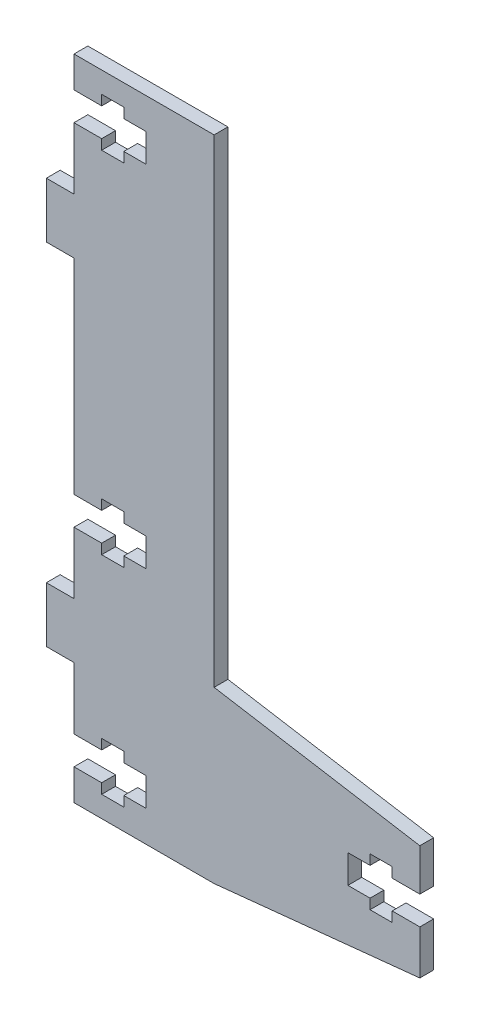
SolidWorks part; units mm, degrees
ref_plane "前视基准面" through (0, 0, 0) normal (0, 0, 1) x (1, 0, 0)
ref_plane "上视基准面" through (0, 0, 0) normal (0, 1, 0) x (1, 0, 0)
ref_plane "右视基准面" through (0, 0, 0) normal (1, 0, 0) x (0, 0, -1)
sketch "草图1" plane through (0, 0, 0) normal (0, 0, 1) x (1, 0, 0)
  line L0 (0, 121.6328) -> (0, -39.6672) construction
  line L1 (0, 38.9328) -> (4, 38.9328)
  line L6 (4, 38.9328) -> (4, 37.4828)
  line L7 (4, 37.4828) -> (7.2, 37.4828)
  line L12 (7.2, 37.4828) -> (7.2, 38.9328)
  line L13 (7.2, 38.9328) -> (10.4, 38.9328)
  line L14 (10.4, 38.9328) -> (10.4, 43.0328)
  line L15 (0, 40.9828) -> (10.4, 40.9828) construction
  line L16 (7.2, 43.0328) -> (10.4, 43.0328)
  line L17 (7.2, 44.4828) -> (7.2, 43.0328)
  line L18 (4, 44.4828) -> (7.2, 44.4828)
  line L19 (4, 43.0328) -> (4, 44.4828)
  line L20 (0, 43.0328) -> (4, 43.0328)
  line L21 (0, 43.0328) -> (0, 47.5328)
  line L22 (0, 47.5328) -> (20.2564, 47.5328)
  line L24 (20.2564, -46.2172) -> (0, -46.2172)
  line L25 (0, -41.7172) -> (4, -41.7172)
  line L26 (4, -41.7172) -> (4, -43.1672)
  line L27 (4, -43.1672) -> (7.2, -43.1672)
  line L28 (7.2, -43.1672) -> (7.2, -41.7172)
  line L29 (7.2, -41.7172) -> (10.4, -41.7172)
  line L30 (10.4, -41.7172) -> (10.4, -37.6172)
  line L31 (0, -39.6672) -> (10.4, -39.6672) construction
  line L32 (7.2, -37.6172) -> (10.4, -37.6172)
  line L33 (7.2, -36.1672) -> (7.2, -37.6172)
  line L34 (4, -36.1672) -> (7.2, -36.1672)
  line L35 (4, -37.6172) -> (4, -36.1672)
  line L36 (0, -37.6172) -> (4, -37.6172)
  line L37 (0, -28.6672) -> (-4, -28.6672)
  line L38 (-4, -28.6672) -> (-4, -20.6672)
  line L39 (-4, -20.6672) -> (0, -20.6672)
  line L40 (-4, -24.6672) -> (0, -24.6672) construction
  line L41 (0, -9.6672) -> (10.4, -9.6672) construction
  line L42 (0, -11.7172) -> (4, -11.7172)
  line L43 (4, -11.7172) -> (4, -13.1672)
  line L44 (4, -13.1672) -> (7.2, -13.1672)
  line L45 (7.2, -13.1672) -> (7.2, -11.7172)
  line L46 (7.2, -11.7172) -> (10.4, -11.7172)
  line L47 (10.4, -7.6172) -> (10.4, -11.7172)
  line L48 (7.2, -7.6172) -> (10.4, -7.6172)
  line L49 (7.2, -6.1672) -> (7.2, -7.6172)
  line L50 (4, -6.1672) -> (7.2, -6.1672)
  line L51 (4, -7.6172) -> (4, -6.1672)
  line L52 (0, -7.6172) -> (4, -7.6172)
  line L53 (0, -11.7172) -> (0, -20.6672)
  line L54 (0, -28.6672) -> (0, -37.6172)
  line L55 (0, 29.9828) -> (-4, 29.9828)
  line L56 (-4, 29.9828) -> (-4, 21.9828)
  line L57 (-4, 21.9828) -> (0, 21.9828)
  line L58 (-4, 25.9828) -> (0, 25.9828) construction
  line L59 (0, 38.9328) -> (0, 29.9828)
  line L60 (0, 21.9828) -> (0, -7.6172)
  line L61 (0, -41.7172) -> (0, -46.2172)
  line L62 (50, -32.6671) -> (46, -32.6671)
  line L67 (50, -36.7671) -> (50, -32.6671) construction
  line L68 (46, -32.6671) -> (46, -31.2171)
  line L69 (46, -31.2171) -> (42.8, -31.2171)
  line L70 (42.8, -31.2171) -> (42.8, -32.6671)
  line L71 (42.8, -32.6671) -> (39.6, -32.6671)
  line L72 (39.6, -32.6671) -> (39.6, -36.7671)
  line L73 (50, -34.7171) -> (39.6, -34.7171) construction
  line L74 (42.8, -36.7671) -> (39.6, -36.7671)
  line L75 (42.8, -38.2171) -> (42.8, -36.7671)
  line L76 (46, -38.2171) -> (42.8, -38.2171)
  line L77 (46, -36.7671) -> (46, -38.2171)
  line L78 (50, -36.7671) -> (46, -36.7671)
  line L81 (20.2564, 47.5328) -> (20.2564, -21.6428)
  line L91 (50, -32.6671) -> (50, -26.6027)
  line L92 (50, -26.6027) -> (20.2564, -21.6428)
  line L93 (50, -36.7671) -> (50, -43.1672)
  line L94 (50, -43.1672) -> (20.2564, -46.2172)
  dimension "D2" = 4
  dimension "D5" = 4
  dimension "D1" = 80.65
  dimension "D3" = 3.2
  dimension "D4" = 2.05
  dimension "D6" = 3.2
  dimension "D8" = 4.1
  dimension "D9" = 7
  dimension "D10" = 15
  dimension "D11" = 4
  dimension "D12" = 8
  dimension "D13" = 15
  dimension "D14" = 8
  dimension "D15" = 4.5
extrude "凸台-拉伸1" add sketch "草图1" along normal blind 2
sketch "草图2" plane through (0, 0, 0) normal (-1, 0, 0) x (0, 0, 1)
  line L0 (1, 38.9328) -> (1, 43.0328)
  line L1 (2, 38.9328) -> (0, 38.9328) construction
  line L2 (2, 43.0328) -> (0, 43.0328) construction
  circle A0 centre (1, 40.9828) radius 2.05
